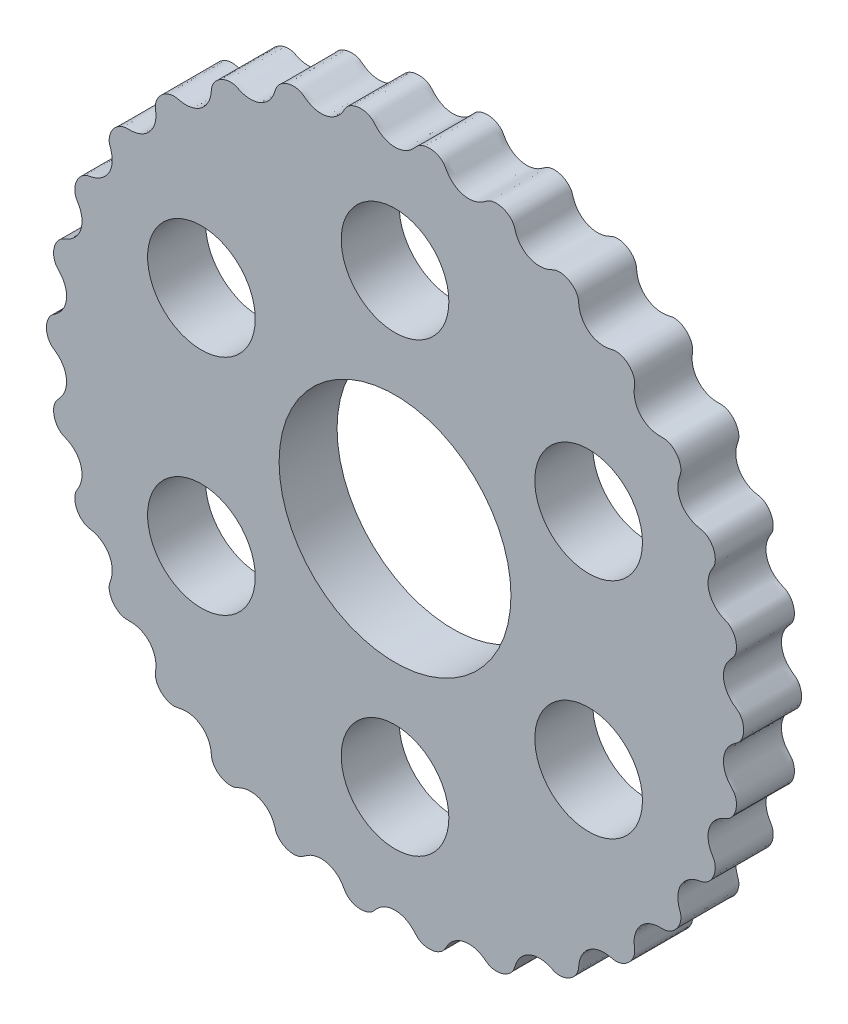
SolidWorks part; units mm, degrees
ref_plane "Front Plane" through (0, 0, 0) normal (0, 0, 1) x (1, 0, 0)
ref_plane "Top Plane" through (0, 0, 0) normal (0, 1, 0) x (1, 0, 0)
ref_plane "Right Plane" through (0, 0, 0) normal (1, 0, 0) x (0, 0, -1)
curve "Curve1"
sketch "Sketch1" plane through (0, 0, 0) normal (0, 0, 1) x (1, 0, 0)
  spline S0 degree 3 poles (1.5393, 40.2126) (0, 39.6745) (-1.5393, 40.2126) (-2.2507, 40.8811) (-2.5061, 41.1764) (-2.6357, 41.3187) (-2.7477, 41.4234) (-2.8793, 41.5246) (-3.0465, 41.6272) (-3.2548, 41.7248) (-3.5028, 41.8074) (-3.7839, 41.865) (-4.0877, 41.8894) (-4.4013, 41.8758) (-4.7109, 41.8238) (-5.003, 41.7368) (-5.266, 41.6221) (-5.4914, 41.4897) (-5.6748, 41.3509) (-5.8171, 41.2159) (-5.9248, 41.0895) (-6.0125, 40.9638) (-6.1097, 40.7977) (-6.2982, 40.4556) (-6.855, 39.6539) (-8.2488, 38.8075) (-9.8664, 39.0138) (-10.7011, 39.5198) (-11.0124, 39.7556) (-11.1688, 39.8678) (-11.3, 39.947) (-11.4498, 40.0186) (-11.6347, 40.0841) (-11.8588, 40.1363) (-12.1185, 40.1655) (-12.4054, 40.1634) (-12.7077, 40.1241) (-13.0116, 40.0457) (-13.3036, 39.9304) (-13.5712, 39.7846) (-13.8046, 39.6177) (-13.9976, 39.4413) (-14.1482, 39.2674) (-14.2592, 39.1058) (-14.3383, 38.9598) (-14.398, 38.8186) (-14.4585, 38.6359) (-14.5717, 38.2621) (-14.9497, 37.3621) (-16.1371, 36.2445) (-17.7622, 36.1099) (-18.6839, 36.4313) (-19.0374, 36.5972) (-19.2137, 36.6745) (-19.3585, 36.7246) (-19.52, 36.7635) (-19.7144, 36.7892) (-19.9444, 36.7936) (-20.2046, 36.7683) (-20.4848, 36.7065) (-20.7722, 36.6052) (-21.0533, 36.4653) (-21.3149, 36.2919) (-21.5464, 36.0936) (-21.74, 35.8818) (-21.892, 35.6692) (-22.0032, 35.4678) (-22.0782, 35.2865) (-22.1252, 35.1273) (-22.1542, 34.9768) (-22.1754, 34.7855) (-22.2085, 34.3964) (-22.391, 33.4375) (-23.3201, 32.0974) (-24.8817, 31.6279) (-25.8501, 31.7506) (-26.2304, 31.8394) (-26.4189, 31.8783) (-26.571, 31.8972) (-26.737, 31.9017) (-26.9325, 31.8864) (-27.1584, 31.8429) (-27.4076, 31.764) (-27.6689, 31.6453) (-27.929, 31.4865) (-28.1748, 31.2912) (-28.3946, 31.0672) (-28.5798, 30.8251) (-28.7251, 30.5777) (-28.8297, 30.3381) (-28.8965, 30.118) (-28.9322, 29.9251) (-28.9451, 29.7596) (-28.9421, 29.6064) (-28.9231, 29.4148) (-28.8746, 29.0273) (-28.8538, 28.0514) (-29.4839, 26.5474) (-30.9138, 25.7636) (-31.8865, 25.6822) (-32.277, 25.69) (-32.4695, 25.6889) (-32.6222, 25.6758) (-32.7854, 25.6457) (-32.9735, 25.59) (-33.1855, 25.5005) (-33.4128, 25.3715) (-33.6437, 25.2011) (-33.8651, 24.9917) (-34.0649, 24.7496) (-34.2334, 24.4847) (-34.3642, 24.2094) (-34.4549, 23.9372) (-34.5073, 23.6811) (-34.5269, 23.4519) (-34.5217, 23.2559) (-34.4999, 23.0913) (-34.4652, 22.942) (-34.4068, 22.7586) (-34.2787, 22.3897) (-34.0555, 21.4394) (-34.3591, 19.8373) (-35.5948, 18.7732) (-36.5294, 18.4914) (-36.9129, 18.4179) (-37.1009, 18.3767) (-37.2476, 18.3322) (-37.401, 18.2688) (-37.5734, 18.1752) (-37.7621, 18.0436) (-37.9577, 17.8702) (-38.1481, 17.6555) (-38.3211, 17.4046) (-38.4662, 17.1263) (-38.576, 16.8322) (-38.6467, 16.5357) (-38.6788, 16.2506) (-38.6768, 15.9892) (-38.6484, 15.7609) (-38.6025, 15.5702) (-38.547, 15.4137) (-38.482, 15.2749) (-38.3867, 15.1077) (-38.1847, 14.7734) (-37.7688, 13.8904) (-37.7327, 12.2601) (-38.7201, 10.9624) (-39.5757, 10.4924) (-39.9356, 10.3408) (-40.1109, 10.2614) (-40.2451, 10.1874) (-40.382, 10.0934) (-40.5312, 9.9661) (-40.6884, 9.7981) (-40.8437, 9.5878) (-40.9852, 9.3383) (-41.1023, 9.0569) (-41.1864, 8.7544) (-41.2326, 8.4439) (-41.2401, 8.1393) (-41.2123, 7.8537) (-41.156, 7.5984) (-41.0807, 7.381) (-40.9962, 7.204) (-40.9093, 7.0625) (-40.8169, 6.9403) (-40.6889, 6.7965) (-40.4219, 6.5116) (-39.8314, 5.7343) (-39.4572, 4.1471) (-40.1532, 2.6725) (-40.8924, 2.0349) (-41.2128, 1.8117) (-41.3679, 1.6977) (-41.4837, 1.5973) (-41.5981, 1.477) (-41.7176, 1.3214) (-41.8364, 1.1244) (-41.9445, 0.8864) (-42.0312, 0.6129) (-42.0872, 0.3133) (-42.1065, 0) (-42.0872, -0.3133) (-42.0312, -0.6129) (-41.9445, -0.8864) (-41.8364, -1.1244) (-41.7176, -1.3214) (-41.5981, -1.477) (-41.4837, -1.5973) (-41.3679, -1.6977) (-41.2128, -1.8117) (-40.8924, -2.0349) (-40.1532, -2.6725) (-39.4572, -4.1471) (-39.8314, -5.7343) (-40.4219, -6.5116) (-40.6889, -6.7965) (-40.8169, -6.9403) (-40.9093, -7.0625) (-40.9962, -7.204) (-41.0807, -7.381) (-41.156, -7.5984) (-41.2123, -7.8537) (-41.2401, -8.1393) (-41.2326, -8.4439) (-41.1864, -8.7544) (-41.1023, -9.0569) (-40.9852, -9.3383) (-40.8437, -9.5878) (-40.6884, -9.7981) (-40.5312, -9.9661) (-40.382, -10.0934) (-40.2451, -10.1874) (-40.1109, -10.2614) (-39.9356, -10.3408) (-39.5757, -10.4924) (-38.7201, -10.9624) (-37.7327, -12.2601) (-37.7688, -13.8904) (-38.1847, -14.7734) (-38.3867, -15.1077) (-38.482, -15.2749) (-38.547, -15.4137) (-38.6025, -15.5702) (-38.6484, -15.7609) (-38.6768, -15.9892) (-38.6788, -16.2506) (-38.6467, -16.5357) (-38.576, -16.8322) (-38.4662, -17.1263) (-38.3211, -17.4046) (-38.1481, -17.6555) (-37.9577, -17.8702) (-37.7621, -18.0436) (-37.5734, -18.1752) (-37.401, -18.2688) (-37.2476, -18.3322) (-37.1009, -18.3767) (-36.9129, -18.4179) (-36.5294, -18.4914) (-35.5948, -18.7732) (-34.3591, -19.8373) (-34.0555, -21.4394) (-34.2787, -22.3897) (-34.4068, -22.7586) (-34.4652, -22.942) (-34.4999, -23.0913) (-34.5217, -23.2559) (-34.5269, -23.4519) (-34.5073, -23.6811) (-34.4549, -23.9372) (-34.3642, -24.2094) (-34.2334, -24.4847) (-34.0649, -24.7496) (-33.8651, -24.9917) (-33.6437, -25.2011) (-33.4128, -25.3715) (-33.1855, -25.5005) (-32.9735, -25.59) (-32.7854, -25.6457) (-32.6222, -25.6758) (-32.4695, -25.6889) (-32.277, -25.69) (-31.8865, -25.6822) (-30.9138, -25.7636) (-29.4839, -26.5474) (-28.8538, -28.0514) (-28.8746, -29.0273) (-28.9231, -29.4148) (-28.9421, -29.6064) (-28.9451, -29.7596) (-28.9322, -29.9251) (-28.8965, -30.118) (-28.8297, -30.3381) (-28.7251, -30.5777) (-28.5798, -30.8251) (-28.3946, -31.0672) (-28.1748, -31.2912) (-27.929, -31.4865) (-27.6689, -31.6453) (-27.4076, -31.764) (-27.1584, -31.8429) (-26.9325, -31.8864) (-26.737, -31.9017) (-26.571, -31.8972) (-26.4189, -31.8783) (-26.2304, -31.8394) (-25.8501, -31.7506) (-24.8817, -31.6279) (-23.3201, -32.0974) (-22.391, -33.4375) (-22.2085, -34.3964) (-22.1754, -34.7855) (-22.1542, -34.9768) (-22.1252, -35.1273) (-22.0782, -35.2865) (-22.0032, -35.4678) (-21.892, -35.6692) (-21.74, -35.8818) (-21.5464, -36.0936) (-21.3149, -36.2919) (-21.0533, -36.4653) (-20.7722, -36.6052) (-20.4848, -36.7065) (-20.2046, -36.7683) (-19.9444, -36.7936) (-19.7144, -36.7892) (-19.52, -36.7635) (-19.3585, -36.7246) (-19.2137, -36.6745) (-19.0374, -36.5972) (-18.6839, -36.4313) (-17.7622, -36.1099) (-16.1371, -36.2445) (-14.9497, -37.3621) (-14.5717, -38.2621) (-14.4585, -38.6359) (-14.398, -38.8186) (-14.3383, -38.9598) (-14.2592, -39.1058) (-14.1482, -39.2674) (-13.9976, -39.4413) (-13.8046, -39.6177) (-13.5712, -39.7846) (-13.3036, -39.9304) (-13.0116, -40.0457) (-12.7077, -40.1241) (-12.4054, -40.1634) (-12.1185, -40.1655) (-11.8588, -40.1363) (-11.6347, -40.0841) (-11.4498, -40.0186) (-11.3, -39.947) (-11.1688, -39.8678) (-11.0124, -39.7556) (-10.7011, -39.5198) (-9.8664, -39.0138) (-8.2488, -38.8075) (-6.855, -39.6539) (-6.2982, -40.4556) (-6.1097, -40.7977) (-6.0125, -40.9638) (-5.9248, -41.0895) (-5.8171, -41.2159) (-5.6748, -41.3509) (-5.4914, -41.4897) (-5.266, -41.6221) (-5.003, -41.7368) (-4.7109, -41.8238) (-4.4013, -41.8758) (-4.0877, -41.8894) (-3.7839, -41.865) (-3.5028, -41.8074) (-3.2548, -41.7248) (-3.0465, -41.6272) (-2.8793, -41.5246) (-2.7477, -41.4234) (-2.6357, -41.3187) (-2.5061, -41.1764) (-2.2507, -40.8811) (-1.5393, -40.2126) (0, -39.6745) (1.5393, -40.2126) (2.2507, -40.8811) (2.5061, -41.1764) (2.6357, -41.3187) (2.7477, -41.4234) (2.8793, -41.5246) (3.0465, -41.6272) (3.2548, -41.7248) (3.5028, -41.8074) (3.7839, -41.865) (4.0877, -41.8894) (4.4013, -41.8758) (4.7109, -41.8238) (5.003, -41.7368) (5.266, -41.6221) (5.4914, -41.4897) (5.6748, -41.3509) (5.8171, -41.2159) (5.9248, -41.0895) (6.0125, -40.9638) (6.1097, -40.7977) (6.2982, -40.4556) (6.855, -39.6539) (8.2488, -38.8075) (9.8664, -39.0138) (10.7011, -39.5198) (11.0124, -39.7556) (11.1688, -39.8678) (11.3, -39.947) (11.4498, -40.0186) (11.6347, -40.0841) (11.8588, -40.1363) (12.1185, -40.1655) (12.4054, -40.1634) (12.7077, -40.1241) (13.0116, -40.0457) (13.3036, -39.9304) (13.5712, -39.7846) (13.8046, -39.6177) (13.9976, -39.4413) (14.1482, -39.2674) (14.2592, -39.1058) (14.3383, -38.9598) (14.398, -38.8186) (14.4585, -38.6359) (14.5717, -38.2621) (14.9497, -37.3621) (16.1371, -36.2445) (17.7622, -36.1099) (18.6839, -36.4313) (19.0374, -36.5972) (19.2137, -36.6745) (19.3585, -36.7246) (19.52, -36.7635) (19.7144, -36.7892) (19.9444, -36.7936) (20.2046, -36.7683) (20.4848, -36.7065) (20.7722, -36.6052) (21.0533, -36.4653) (21.3149, -36.2919) (21.5464, -36.0936) (21.74, -35.8818) (21.892, -35.6692) (22.0032, -35.4678) (22.0782, -35.2865) (22.1252, -35.1273) (22.1542, -34.9768) (22.1754, -34.7855) (22.2085, -34.3964) (22.391, -33.4375) (23.3201, -32.0974) (24.8817, -31.6279) (25.8501, -31.7506) (26.2304, -31.8394) (26.4189, -31.8783) (26.571, -31.8972) (26.737, -31.9017) (26.9325, -31.8864) (27.1584, -31.8429) (27.4076, -31.764) (27.6689, -31.6453) (27.929, -31.4865) (28.1748, -31.2912) (28.3946, -31.0672) (28.5798, -30.8251) (28.7251, -30.5777) (28.8297, -30.3381) (28.8965, -30.118) (28.9322, -29.9251) (28.9451, -29.7596) (28.9421, -29.6064) (28.9231, -29.4148) (28.8746, -29.0273) (28.8538, -28.0514) (29.4839, -26.5474) (30.9138, -25.7636) (31.8865, -25.6822) (32.277, -25.69) (32.4695, -25.6889) (32.6222, -25.6758) (32.7854, -25.6457) (32.9735, -25.59) (33.1855, -25.5005) (33.4128, -25.3715) (33.6437, -25.2011) (33.8651, -24.9917) (34.0649, -24.7496) (34.2334, -24.4847) (34.3642, -24.2094) (34.4549, -23.9372) (34.5073, -23.6811) (34.5269, -23.4519) (34.5217, -23.2559) (34.4999, -23.0913) (34.4652, -22.942) (34.4068, -22.7586) (34.2787, -22.3897) (34.0555, -21.4394) (34.3591, -19.8373) (35.5948, -18.7732) (36.5294, -18.4914) (36.9129, -18.4179) (37.1009, -18.3767) (37.2476, -18.3322) (37.401, -18.2688) (37.5734, -18.1752) (37.7621, -18.0436) (37.9577, -17.8702) (38.1481, -17.6555) (38.3211, -17.4046) (38.4662, -17.1263) (38.576, -16.8322) (38.6467, -16.5357) (38.6788, -16.2506) (38.6768, -15.9892) (38.6484, -15.7609) (38.6025, -15.5702) (38.547, -15.4137) (38.482, -15.2749) (38.3867, -15.1077) (38.1847, -14.7734) (37.7688, -13.8904) (37.7327, -12.2601) (38.7201, -10.9624) (39.5757, -10.4924) (39.9356, -10.3408) (40.1109, -10.2614) (40.2451, -10.1874) (40.382, -10.0934) (40.5312, -9.9661) (40.6884, -9.7981) (40.8437, -9.5878) (40.9852, -9.3383) (41.1023, -9.0569) (41.1864, -8.7544) (41.2326, -8.4439) (41.2401, -8.1393) (41.2123, -7.8537) (41.156, -7.5984) (41.0807, -7.381) (40.9962, -7.204) (40.9093, -7.0625) (40.8169, -6.9403) (40.6889, -6.7965) (40.4219, -6.5116) (39.8314, -5.7343) (39.4572, -4.1471) (40.1532, -2.6725) (40.8924, -2.0349) (41.2128, -1.8117) (41.3679, -1.6977) (41.4837, -1.5973) (41.5981, -1.477) (41.7176, -1.3214) (41.8364, -1.1244) (41.9445, -0.8864) (42.0312, -0.6129) (42.0872, -0.3133) (42.1065, 0) (42.0872, 0.3133) (42.0312, 0.6129) (41.9445, 0.8864) (41.8364, 1.1244) (41.7176, 1.3214) (41.5981, 1.477) (41.4837, 1.5973) (41.3679, 1.6977) (41.2128, 1.8117) (40.8924, 2.0349) (40.1532, 2.6725) (39.4572, 4.1471) (39.8314, 5.7343) (40.4219, 6.5116) (40.6889, 6.7965) (40.8169, 6.9403) (40.9093, 7.0625) (40.9962, 7.204) (41.0807, 7.381) (41.156, 7.5984) (41.2123, 7.8537) (41.2401, 8.1393) (41.2326, 8.4439) (41.1864, 8.7544) (41.1023, 9.0569) (40.9852, 9.3383) (40.8437, 9.5878) (40.6884, 9.7981) (40.5312, 9.9661) (40.382, 10.0934) (40.2451, 10.1874) (40.1109, 10.2614) (39.9356, 10.3408) (39.5757, 10.4924) (38.7201, 10.9624) (37.7327, 12.2601) (37.7688, 13.8904) (38.1847, 14.7734) (38.3867, 15.1077) (38.482, 15.2749) (38.547, 15.4137) (38.6025, 15.5702) (38.6484, 15.7609) (38.6768, 15.9892) (38.6788, 16.2506) (38.6467, 16.5357) (38.576, 16.8322) (38.4662, 17.1263) (38.3211, 17.4046) (38.1481, 17.6555) (37.9577, 17.8702) (37.7621, 18.0436) (37.5734, 18.1752) (37.401, 18.2688) (37.2476, 18.3322) (37.1009, 18.3767) (36.9129, 18.4179) (36.5294, 18.4914) (35.5948, 18.7732) (34.3591, 19.8373) (34.0555, 21.4394) (34.2787, 22.3897) (34.4068, 22.7586) (34.4652, 22.942) (34.4999, 23.0913) (34.5217, 23.2559) (34.5269, 23.4519) (34.5073, 23.6811) (34.4549, 23.9372) (34.3642, 24.2094) (34.2334, 24.4847) (34.0649, 24.7496) (33.8651, 24.9917) (33.6437, 25.2011) (33.4128, 25.3715) (33.1855, 25.5005) (32.9735, 25.59) (32.7854, 25.6457) (32.6222, 25.6758) (32.4695, 25.6889) (32.277, 25.69) (31.8865, 25.6822) (30.9138, 25.7636) (29.4839, 26.5474) (28.8538, 28.0514) (28.8746, 29.0273) (28.9231, 29.4148) (28.9421, 29.6064) (28.9451, 29.7596) (28.9322, 29.9251) (28.8965, 30.118) (28.8297, 30.3381) (28.7251, 30.5777) (28.5798, 30.8251) (28.3946, 31.0672) (28.1748, 31.2912) (27.929, 31.4865) (27.6689, 31.6453) (27.4076, 31.764) (27.1584, 31.8429) (26.9325, 31.8864) (26.737, 31.9017) (26.571, 31.8972) (26.4189, 31.8783) (26.2304, 31.8394) (25.8501, 31.7506) (24.8817, 31.6279) (23.3201, 32.0974) (22.391, 33.4375) (22.2085, 34.3964) (22.1754, 34.7855) (22.1542, 34.9768) (22.1252, 35.1273) (22.0782, 35.2865) (22.0032, 35.4678) (21.892, 35.6692) (21.74, 35.8818) (21.5464, 36.0936) (21.3149, 36.2919) (21.0533, 36.4653) (20.7722, 36.6052) (20.4848, 36.7065) (20.2046, 36.7683) (19.9444, 36.7936) (19.7144, 36.7892) (19.52, 36.7635) (19.3585, 36.7246) (19.2137, 36.6745) (19.0374, 36.5972) (18.6839, 36.4313) (17.7622, 36.1099) (16.1371, 36.2445) (14.9497, 37.3621) (14.5717, 38.2621) (14.4585, 38.6359) (14.398, 38.8186) (14.3383, 38.9598) (14.2592, 39.1058) (14.1482, 39.2674) (13.9976, 39.4413) (13.8046, 39.6177) (13.5712, 39.7846) (13.3036, 39.9304) (13.0116, 40.0457) (12.7077, 40.1241) (12.4054, 40.1634) (12.1185, 40.1655) (11.8588, 40.1363) (11.6347, 40.0841) (11.4498, 40.0186) (11.3, 39.947) (11.1688, 39.8678) (11.0124, 39.7556) (10.7011, 39.5198) (9.8664, 39.0138) (8.2488, 38.8075) (6.855, 39.6539) (6.2982, 40.4556) (6.1097, 40.7977) (6.0125, 40.9638) (5.9248, 41.0895) (5.8171, 41.2159) (5.6748, 41.3509) (5.4914, 41.4897) (5.266, 41.6221) (5.003, 41.7368) (4.7109, 41.8238) (4.4013, 41.8758) (4.0877, 41.8894) (3.7839, 41.865) (3.5028, 41.8074) (3.2548, 41.7248) (3.0465, 41.6272) (2.8793, 41.5246) (2.7477, 41.4234) (2.6357, 41.3187) (2.5061, 41.1764) (2.2507, 40.8811) (1.5393, 40.2126) (0, 39.6745) (-1.5393, 40.2126) knots -0.009769 -0.008833 -0.006371 0 0.006371 0.008833 0.009769 0.010295 0.010766 0.011307 0.01196 0.012732 0.013613 0.01458 0.015608 0.016667 0.017726 0.018753 0.019721 0.020601 0.021373 0.022027 0.022568 0.023039 0.023565 0.024501 0.026962 0.033333 0.039705 0.042166 0.043102 0.043628 0.044099 0.04464 0.045293 0.046066 0.046946 0.047913 0.048941 0.05 0.051059 0.052087 0.053054 0.053934 0.054707 0.05536 0.055901 0.056372 0.056898 0.057834 0.060295 0.066667 0.073038 0.075499 0.076435 0.076961 0.077432 0.077973 0.078627 0.079399 0.080279 0.081247 0.082274 0.083333 0.084392 0.08542 0.086387 0.087268 0.08804 0.088693 0.089234 0.089705 0.090231 0.091167 0.093629 0.1 0.106371 0.108833 0.109769 0.110295 0.110766 0.111307 0.11196 0.112732 0.113613 0.11458 0.115608 0.116667 0.117726 0.118753 0.119721 0.120601 0.121373 0.122027 0.122568 0.123039 0.123565 0.124501 0.126962 0.133333 0.139705 0.142166 0.143102 0.143628 0.144099 0.14464 0.145293 0.146066 0.146946 0.147913 0.148941 0.15 0.151059 0.152087 0.153054 0.153934 0.154707 0.15536 0.155901 0.156372 0.156898 0.157834 0.160295 0.166667 0.173038 0.175499 0.176435 0.176961 0.177432 0.177973 0.178627 0.179399 0.180279 0.181247 0.182274 0.183333 0.184392 0.18542 0.186387 0.187268 0.18804 0.188693 0.189234 0.189705 0.190231 0.191167 0.193629 0.2 0.206371 0.208833 0.209769 0.210295 0.210766 0.211306 0.21196 0.212732 0.213613 0.21458 0.215608 0.216667 0.217726 0.218753 0.219721 0.220601 0.221373 0.222027 0.222568 0.223039 0.223565 0.224501 0.226962 0.233333 0.239705 0.242166 0.243102 0.243628 0.244099 0.24464 0.245293 0.246066 0.246946 0.247913 0.248941 0.25 0.251059 0.252087 0.253054 0.253934 0.254707 0.25536 0.255901 0.256372 0.256898 0.257834 0.260295 0.266667 0.273038 0.275499 0.276435 0.276961 0.277432 0.277973 0.278627 0.279399 0.280279 0.281247 0.282274 0.283333 0.284392 0.28542 0.286387 0.287268 0.28804 0.288694 0.289234 0.289705 0.290231 0.291167 0.293629 0.3 0.306371 0.308833 0.309769 0.310295 0.310766 0.311307 0.31196 0.312732 0.313613 0.31458 0.315608 0.316667 0.317726 0.318753 0.319721 0.320601 0.321373 0.322027 0.322568 0.323039 0.323565 0.324501 0.326962 0.333333 0.339705 0.342166 0.343102 0.343628 0.344099 0.34464 0.345293 0.346066 0.346946 0.347913 0.348941 0.35 0.351059 0.352087 0.353054 0.353934 0.354707 0.35536 0.355901 0.356372 0.356898 0.357834 0.360295 0.366667 0.373038 0.375499 0.376435 0.376961 0.377432 0.377973 0.378627 0.379399 0.380279 0.381247 0.382274 0.383333 0.384392 0.38542 0.386387 0.387268 0.38804 0.388693 0.389234 0.389705 0.390231 0.391167 0.393629 0.4 0.406371 0.408833 0.409769 0.410295 0.410766 0.411307 0.41196 0.412732 0.413613 0.41458 0.415608 0.416667 0.417726 0.418753 0.419721 0.420601 0.421373 0.422027 0.422568 0.423039 0.423565 0.424501 0.426962 0.433333 0.439705 0.442166 0.443102 0.443628 0.444099 0.44464 0.445293 0.446066 0.446946 0.447913 0.448941 0.45 0.451059 0.452087 0.453054 0.453934 0.454707 0.45536 0.455901 0.456372 0.456898 0.457834 0.460295 0.466667 0.473038 0.475499 0.476435 0.476961 0.477432 0.477973 0.478627 0.479399 0.480279 0.481247 0.482274 0.483333 0.484392 0.48542 0.486387 0.487268 0.48804 0.488693 0.489234 0.489705 0.490231 0.491167 0.493629 0.5 0.506371 0.508833 0.509769 0.510295 0.510766 0.511307 0.51196 0.512732 0.513613 0.51458 0.515608 0.516667 0.517726 0.518753 0.519721 0.520601 0.521373 0.522027 0.522568 0.523039 0.523565 0.524501 0.526962 0.533333 0.539705 0.542166 0.543102 0.543628 0.544099 0.54464 0.545293 0.546066 0.546946 0.547913 0.548941 0.55 0.551059 0.552087 0.553054 0.553934 0.554707 0.55536 0.555901 0.556372 0.556898 0.557834 0.560295 0.566667 0.573038 0.575499 0.576435 0.576961 0.577432 0.577973 0.578627 0.579399 0.580279 0.581247 0.582274 0.583333 0.584392 0.58542 0.586387 0.587268 0.58804 0.588693 0.589234 0.589705 0.590231 0.591167 0.593629 0.6 0.606371 0.608833 0.609769 0.610295 0.610766 0.611307 0.61196 0.612732 0.613613 0.61458 0.615608 0.616667 0.617726 0.618753 0.619721 0.620601 0.621373 0.622027 0.622568 0.623039 0.623565 0.624501 0.626962 0.633333 0.639705 0.642166 0.643102 0.643628 0.644099 0.64464 0.645293 0.646066 0.646946 0.647913 0.648941 0.65 0.651059 0.652087 0.653054 0.653934 0.654707 0.65536 0.655901 0.656372 0.656898 0.657834 0.660295 0.666667 0.673038 0.675499 0.676435 0.676961 0.677432 0.677973 0.678627 0.679399 0.680279 0.681247 0.682274 0.683333 0.684392 0.68542 0.686387 0.687268 0.68804 0.688693 0.689234 0.689705 0.690231 0.691167 0.693629 0.7 0.706371 0.708833 0.709769 0.710295 0.710766 0.711306 0.71196 0.712732 0.713613 0.71458 0.715608 0.716667 0.717726 0.718753 0.719721 0.720601 0.721373 0.722027 0.722568 0.723039 0.723565 0.724501 0.726962 0.733333 0.739705 0.742166 0.743102 0.743628 0.744099 0.74464 0.745293 0.746066 0.746946 0.747913 0.748941 0.75 0.751059 0.752087 0.753054 0.753934 0.754707 0.75536 0.755901 0.756372 0.756898 0.757834 0.760295 0.766667 0.773038 0.775499 0.776435 0.776961 0.777432 0.777973 0.778627 0.779399 0.780279 0.781247 0.782274 0.783333 0.784392 0.78542 0.786387 0.787268 0.78804 0.788694 0.789234 0.789705 0.790231 0.791167 0.793629 0.8 0.806371 0.808833 0.809769 0.810295 0.810766 0.811307 0.81196 0.812732 0.813613 0.81458 0.815608 0.816667 0.817726 0.818753 0.819721 0.820601 0.821373 0.822027 0.822568 0.823039 0.823565 0.824501 0.826962 0.833333 0.839705 0.842166 0.843102 0.843628 0.844099 0.84464 0.845293 0.846066 0.846946 0.847913 0.848941 0.85 0.851059 0.852087 0.853054 0.853934 0.854707 0.85536 0.855901 0.856372 0.856898 0.857834 0.860295 0.866667 0.873038 0.875499 0.876435 0.876961 0.877432 0.877973 0.878627 0.879399 0.880279 0.881247 0.882274 0.883333 0.884392 0.88542 0.886387 0.887268 0.88804 0.888693 0.889234 0.889705 0.890231 0.891167 0.893629 0.9 0.906371 0.908833 0.909769 0.910295 0.910766 0.911307 0.91196 0.912732 0.913613 0.91458 0.915608 0.916667 0.917726 0.918753 0.919721 0.920601 0.921373 0.922027 0.922568 0.923039 0.923565 0.924501 0.926962 0.933333 0.939705 0.942166 0.943102 0.943628 0.944099 0.94464 0.945293 0.946066 0.946946 0.947913 0.948941 0.95 0.951059 0.952087 0.953054 0.953934 0.954707 0.95536 0.955901 0.956372 0.956898 0.957834 0.960295 0.966667 0.973038 0.975499 0.976435 0.976961 0.977432 0.977973 0.978627 0.979399 0.980279 0.981247 0.982274 0.983333 0.984392 0.98542 0.986387 0.987268 0.98804 0.988693 0.989234 0.989705 0.990231 0.991167 0.993629 1 1.006371 1.008833 1.009769 only from (0, 39.9) to (0, 39.9) construction
  spline S1 degree 3 poles (1.5393, 40.2126) (0, 39.6745) (-1.5393, 40.2126) (-2.2507, 40.8811) (-2.5061, 41.1764) (-2.6357, 41.3187) (-2.7477, 41.4234) (-2.8793, 41.5246) (-3.0465, 41.6272) (-3.2548, 41.7248) (-3.5028, 41.8074) (-3.7839, 41.865) (-4.0877, 41.8894) (-4.4013, 41.8758) (-4.7109, 41.8238) (-5.003, 41.7368) (-5.266, 41.6221) (-5.4914, 41.4897) (-5.6748, 41.3509) (-5.8171, 41.2159) (-5.9248, 41.0895) (-6.0125, 40.9638) (-6.1097, 40.7977) (-6.2982, 40.4556) (-6.855, 39.6539) (-8.2488, 38.8075) (-9.8664, 39.0138) (-10.7011, 39.5198) (-11.0124, 39.7556) (-11.1688, 39.8678) (-11.3, 39.947) (-11.4498, 40.0186) (-11.6347, 40.0841) (-11.8588, 40.1363) (-12.1185, 40.1655) (-12.4054, 40.1634) (-12.7077, 40.1241) (-13.0116, 40.0457) (-13.3036, 39.9304) (-13.5712, 39.7846) (-13.8046, 39.6177) (-13.9976, 39.4413) (-14.1482, 39.2674) (-14.2592, 39.1058) (-14.3383, 38.9598) (-14.398, 38.8186) (-14.4585, 38.6359) (-14.5717, 38.2621) (-14.9497, 37.3621) (-16.1371, 36.2445) (-17.7622, 36.1099) (-18.6839, 36.4313) (-19.0374, 36.5972) (-19.2137, 36.6745) (-19.3585, 36.7246) (-19.52, 36.7635) (-19.7144, 36.7892) (-19.9444, 36.7936) (-20.2046, 36.7683) (-20.4848, 36.7065) (-20.7722, 36.6052) (-21.0533, 36.4653) (-21.3149, 36.2919) (-21.5464, 36.0936) (-21.74, 35.8818) (-21.892, 35.6692) (-22.0032, 35.4678) (-22.0782, 35.2865) (-22.1252, 35.1273) (-22.1542, 34.9768) (-22.1754, 34.7855) (-22.2085, 34.3964) (-22.391, 33.4375) (-23.3201, 32.0974) (-24.8817, 31.6279) (-25.8501, 31.7506) (-26.2304, 31.8394) (-26.4189, 31.8783) (-26.571, 31.8972) (-26.737, 31.9017) (-26.9325, 31.8864) (-27.1584, 31.8429) (-27.4076, 31.764) (-27.6689, 31.6453) (-27.929, 31.4865) (-28.1748, 31.2912) (-28.3946, 31.0672) (-28.5798, 30.8251) (-28.7251, 30.5777) (-28.8297, 30.3381) (-28.8965, 30.118) (-28.9322, 29.9251) (-28.9451, 29.7596) (-28.9421, 29.6064) (-28.9231, 29.4148) (-28.8746, 29.0273) (-28.8538, 28.0514) (-29.4839, 26.5474) (-30.9138, 25.7636) (-31.8865, 25.6822) (-32.277, 25.69) (-32.4695, 25.6889) (-32.6222, 25.6758) (-32.7854, 25.6457) (-32.9735, 25.59) (-33.1855, 25.5005) (-33.4128, 25.3715) (-33.6437, 25.2011) (-33.8651, 24.9917) (-34.0649, 24.7496) (-34.2334, 24.4847) (-34.3642, 24.2094) (-34.4549, 23.9372) (-34.5073, 23.6811) (-34.5269, 23.4519) (-34.5217, 23.2559) (-34.4999, 23.0913) (-34.4652, 22.942) (-34.4068, 22.7586) (-34.2787, 22.3897) (-34.0555, 21.4394) (-34.3591, 19.8373) (-35.5948, 18.7732) (-36.5294, 18.4914) (-36.9129, 18.4179) (-37.1009, 18.3767) (-37.2476, 18.3322) (-37.401, 18.2688) (-37.5734, 18.1752) (-37.7621, 18.0436) (-37.9577, 17.8702) (-38.1481, 17.6555) (-38.3211, 17.4046) (-38.4662, 17.1263) (-38.576, 16.8322) (-38.6467, 16.5357) (-38.6788, 16.2506) (-38.6768, 15.9892) (-38.6484, 15.7609) (-38.6025, 15.5702) (-38.547, 15.4137) (-38.482, 15.2749) (-38.3867, 15.1077) (-38.1847, 14.7734) (-37.7688, 13.8904) (-37.7327, 12.2601) (-38.7201, 10.9624) (-39.5757, 10.4924) (-39.9356, 10.3408) (-40.1109, 10.2614) (-40.2451, 10.1874) (-40.382, 10.0934) (-40.5312, 9.9661) (-40.6884, 9.7981) (-40.8437, 9.5878) (-40.9852, 9.3383) (-41.1023, 9.0569) (-41.1864, 8.7544) (-41.2326, 8.4439) (-41.2401, 8.1393) (-41.2123, 7.8537) (-41.156, 7.5984) (-41.0807, 7.381) (-40.9962, 7.204) (-40.9093, 7.0625) (-40.8169, 6.9403) (-40.6889, 6.7965) (-40.4219, 6.5116) (-39.8314, 5.7343) (-39.4572, 4.1471) (-40.1532, 2.6725) (-40.8924, 2.0349) (-41.2128, 1.8117) (-41.3679, 1.6977) (-41.4837, 1.5973) (-41.5981, 1.477) (-41.7176, 1.3214) (-41.8364, 1.1244) (-41.9445, 0.8864) (-42.0312, 0.6129) (-42.0872, 0.3133) (-42.1065, 0) (-42.0872, -0.3133) (-42.0312, -0.6129) (-41.9445, -0.8864) (-41.8364, -1.1244) (-41.7176, -1.3214) (-41.5981, -1.477) (-41.4837, -1.5973) (-41.3679, -1.6977) (-41.2128, -1.8117) (-40.8924, -2.0349) (-40.1532, -2.6725) (-39.4572, -4.1471) (-39.8314, -5.7343) (-40.4219, -6.5116) (-40.6889, -6.7965) (-40.8169, -6.9403) (-40.9093, -7.0625) (-40.9962, -7.204) (-41.0807, -7.381) (-41.156, -7.5984) (-41.2123, -7.8537) (-41.2401, -8.1393) (-41.2326, -8.4439) (-41.1864, -8.7544) (-41.1023, -9.0569) (-40.9852, -9.3383) (-40.8437, -9.5878) (-40.6884, -9.7981) (-40.5312, -9.9661) (-40.382, -10.0934) (-40.2451, -10.1874) (-40.1109, -10.2614) (-39.9356, -10.3408) (-39.5757, -10.4924) (-38.7201, -10.9624) (-37.7327, -12.2601) (-37.7688, -13.8904) (-38.1847, -14.7734) (-38.3867, -15.1077) (-38.482, -15.2749) (-38.547, -15.4137) (-38.6025, -15.5702) (-38.6484, -15.7609) (-38.6768, -15.9892) (-38.6788, -16.2506) (-38.6467, -16.5357) (-38.576, -16.8322) (-38.4662, -17.1263) (-38.3211, -17.4046) (-38.1481, -17.6555) (-37.9577, -17.8702) (-37.7621, -18.0436) (-37.5734, -18.1752) (-37.401, -18.2688) (-37.2476, -18.3322) (-37.1009, -18.3767) (-36.9129, -18.4179) (-36.5294, -18.4914) (-35.5948, -18.7732) (-34.3591, -19.8373) (-34.0555, -21.4394) (-34.2787, -22.3897) (-34.4068, -22.7586) (-34.4652, -22.942) (-34.4999, -23.0913) (-34.5217, -23.2559) (-34.5269, -23.4519) (-34.5073, -23.6811) (-34.4549, -23.9372) (-34.3642, -24.2094) (-34.2334, -24.4847) (-34.0649, -24.7496) (-33.8651, -24.9917) (-33.6437, -25.2011) (-33.4128, -25.3715) (-33.1855, -25.5005) (-32.9735, -25.59) (-32.7854, -25.6457) (-32.6222, -25.6758) (-32.4695, -25.6889) (-32.277, -25.69) (-31.8865, -25.6822) (-30.9138, -25.7636) (-29.4839, -26.5474) (-28.8538, -28.0514) (-28.8746, -29.0273) (-28.9231, -29.4148) (-28.9421, -29.6064) (-28.9451, -29.7596) (-28.9322, -29.9251) (-28.8965, -30.118) (-28.8297, -30.3381) (-28.7251, -30.5777) (-28.5798, -30.8251) (-28.3946, -31.0672) (-28.1748, -31.2912) (-27.929, -31.4865) (-27.6689, -31.6453) (-27.4076, -31.764) (-27.1584, -31.8429) (-26.9325, -31.8864) (-26.737, -31.9017) (-26.571, -31.8972) (-26.4189, -31.8783) (-26.2304, -31.8394) (-25.8501, -31.7506) (-24.8817, -31.6279) (-23.3201, -32.0974) (-22.391, -33.4375) (-22.2085, -34.3964) (-22.1754, -34.7855) (-22.1542, -34.9768) (-22.1252, -35.1273) (-22.0782, -35.2865) (-22.0032, -35.4678) (-21.892, -35.6692) (-21.74, -35.8818) (-21.5464, -36.0936) (-21.3149, -36.2919) (-21.0533, -36.4653) (-20.7722, -36.6052) (-20.4848, -36.7065) (-20.2046, -36.7683) (-19.9444, -36.7936) (-19.7144, -36.7892) (-19.52, -36.7635) (-19.3585, -36.7246) (-19.2137, -36.6745) (-19.0374, -36.5972) (-18.6839, -36.4313) (-17.7622, -36.1099) (-16.1371, -36.2445) (-14.9497, -37.3621) (-14.5717, -38.2621) (-14.4585, -38.6359) (-14.398, -38.8186) (-14.3383, -38.9598) (-14.2592, -39.1058) (-14.1482, -39.2674) (-13.9976, -39.4413) (-13.8046, -39.6177) (-13.5712, -39.7846) (-13.3036, -39.9304) (-13.0116, -40.0457) (-12.7077, -40.1241) (-12.4054, -40.1634) (-12.1185, -40.1655) (-11.8588, -40.1363) (-11.6347, -40.0841) (-11.4498, -40.0186) (-11.3, -39.947) (-11.1688, -39.8678) (-11.0124, -39.7556) (-10.7011, -39.5198) (-9.8664, -39.0138) (-8.2488, -38.8075) (-6.855, -39.6539) (-6.2982, -40.4556) (-6.1097, -40.7977) (-6.0125, -40.9638) (-5.9248, -41.0895) (-5.8171, -41.2159) (-5.6748, -41.3509) (-5.4914, -41.4897) (-5.266, -41.6221) (-5.003, -41.7368) (-4.7109, -41.8238) (-4.4013, -41.8758) (-4.0877, -41.8894) (-3.7839, -41.865) (-3.5028, -41.8074) (-3.2548, -41.7248) (-3.0465, -41.6272) (-2.8793, -41.5246) (-2.7477, -41.4234) (-2.6357, -41.3187) (-2.5061, -41.1764) (-2.2507, -40.8811) (-1.5393, -40.2126) (0, -39.6745) (1.5393, -40.2126) (2.2507, -40.8811) (2.5061, -41.1764) (2.6357, -41.3187) (2.7477, -41.4234) (2.8793, -41.5246) (3.0465, -41.6272) (3.2548, -41.7248) (3.5028, -41.8074) (3.7839, -41.865) (4.0877, -41.8894) (4.4013, -41.8758) (4.7109, -41.8238) (5.003, -41.7368) (5.266, -41.6221) (5.4914, -41.4897) (5.6748, -41.3509) (5.8171, -41.2159) (5.9248, -41.0895) (6.0125, -40.9638) (6.1097, -40.7977) (6.2982, -40.4556) (6.855, -39.6539) (8.2488, -38.8075) (9.8664, -39.0138) (10.7011, -39.5198) (11.0124, -39.7556) (11.1688, -39.8678) (11.3, -39.947) (11.4498, -40.0186) (11.6347, -40.0841) (11.8588, -40.1363) (12.1185, -40.1655) (12.4054, -40.1634) (12.7077, -40.1241) (13.0116, -40.0457) (13.3036, -39.9304) (13.5712, -39.7846) (13.8046, -39.6177) (13.9976, -39.4413) (14.1482, -39.2674) (14.2592, -39.1058) (14.3383, -38.9598) (14.398, -38.8186) (14.4585, -38.6359) (14.5717, -38.2621) (14.9497, -37.3621) (16.1371, -36.2445) (17.7622, -36.1099) (18.6839, -36.4313) (19.0374, -36.5972) (19.2137, -36.6745) (19.3585, -36.7246) (19.52, -36.7635) (19.7144, -36.7892) (19.9444, -36.7936) (20.2046, -36.7683) (20.4848, -36.7065) (20.7722, -36.6052) (21.0533, -36.4653) (21.3149, -36.2919) (21.5464, -36.0936) (21.74, -35.8818) (21.892, -35.6692) (22.0032, -35.4678) (22.0782, -35.2865) (22.1252, -35.1273) (22.1542, -34.9768) (22.1754, -34.7855) (22.2085, -34.3964) (22.391, -33.4375) (23.3201, -32.0974) (24.8817, -31.6279) (25.8501, -31.7506) (26.2304, -31.8394) (26.4189, -31.8783) (26.571, -31.8972) (26.737, -31.9017) (26.9325, -31.8864) (27.1584, -31.8429) (27.4076, -31.764) (27.6689, -31.6453) (27.929, -31.4865) (28.1748, -31.2912) (28.3946, -31.0672) (28.5798, -30.8251) (28.7251, -30.5777) (28.8297, -30.3381) (28.8965, -30.118) (28.9322, -29.9251) (28.9451, -29.7596) (28.9421, -29.6064) (28.9231, -29.4148) (28.8746, -29.0273) (28.8538, -28.0514) (29.4839, -26.5474) (30.9138, -25.7636) (31.8865, -25.6822) (32.277, -25.69) (32.4695, -25.6889) (32.6222, -25.6758) (32.7854, -25.6457) (32.9735, -25.59) (33.1855, -25.5005) (33.4128, -25.3715) (33.6437, -25.2011) (33.8651, -24.9917) (34.0649, -24.7496) (34.2334, -24.4847) (34.3642, -24.2094) (34.4549, -23.9372) (34.5073, -23.6811) (34.5269, -23.4519) (34.5217, -23.2559) (34.4999, -23.0913) (34.4652, -22.942) (34.4068, -22.7586) (34.2787, -22.3897) (34.0555, -21.4394) (34.3591, -19.8373) (35.5948, -18.7732) (36.5294, -18.4914) (36.9129, -18.4179) (37.1009, -18.3767) (37.2476, -18.3322) (37.401, -18.2688) (37.5734, -18.1752) (37.7621, -18.0436) (37.9577, -17.8702) (38.1481, -17.6555) (38.3211, -17.4046) (38.4662, -17.1263) (38.576, -16.8322) (38.6467, -16.5357) (38.6788, -16.2506) (38.6768, -15.9892) (38.6484, -15.7609) (38.6025, -15.5702) (38.547, -15.4137) (38.482, -15.2749) (38.3867, -15.1077) (38.1847, -14.7734) (37.7688, -13.8904) (37.7327, -12.2601) (38.7201, -10.9624) (39.5757, -10.4924) (39.9356, -10.3408) (40.1109, -10.2614) (40.2451, -10.1874) (40.382, -10.0934) (40.5312, -9.9661) (40.6884, -9.7981) (40.8437, -9.5878) (40.9852, -9.3383) (41.1023, -9.0569) (41.1864, -8.7544) (41.2326, -8.4439) (41.2401, -8.1393) (41.2123, -7.8537) (41.156, -7.5984) (41.0807, -7.381) (40.9962, -7.204) (40.9093, -7.0625) (40.8169, -6.9403) (40.6889, -6.7965) (40.4219, -6.5116) (39.8314, -5.7343) (39.4572, -4.1471) (40.1532, -2.6725) (40.8924, -2.0349) (41.2128, -1.8117) (41.3679, -1.6977) (41.4837, -1.5973) (41.5981, -1.477) (41.7176, -1.3214) (41.8364, -1.1244) (41.9445, -0.8864) (42.0312, -0.6129) (42.0872, -0.3133) (42.1065, 0) (42.0872, 0.3133) (42.0312, 0.6129) (41.9445, 0.8864) (41.8364, 1.1244) (41.7176, 1.3214) (41.5981, 1.477) (41.4837, 1.5973) (41.3679, 1.6977) (41.2128, 1.8117) (40.8924, 2.0349) (40.1532, 2.6725) (39.4572, 4.1471) (39.8314, 5.7343) (40.4219, 6.5116) (40.6889, 6.7965) (40.8169, 6.9403) (40.9093, 7.0625) (40.9962, 7.204) (41.0807, 7.381) (41.156, 7.5984) (41.2123, 7.8537) (41.2401, 8.1393) (41.2326, 8.4439) (41.1864, 8.7544) (41.1023, 9.0569) (40.9852, 9.3383) (40.8437, 9.5878) (40.6884, 9.7981) (40.5312, 9.9661) (40.382, 10.0934) (40.2451, 10.1874) (40.1109, 10.2614) (39.9356, 10.3408) (39.5757, 10.4924) (38.7201, 10.9624) (37.7327, 12.2601) (37.7688, 13.8904) (38.1847, 14.7734) (38.3867, 15.1077) (38.482, 15.2749) (38.547, 15.4137) (38.6025, 15.5702) (38.6484, 15.7609) (38.6768, 15.9892) (38.6788, 16.2506) (38.6467, 16.5357) (38.576, 16.8322) (38.4662, 17.1263) (38.3211, 17.4046) (38.1481, 17.6555) (37.9577, 17.8702) (37.7621, 18.0436) (37.5734, 18.1752) (37.401, 18.2688) (37.2476, 18.3322) (37.1009, 18.3767) (36.9129, 18.4179) (36.5294, 18.4914) (35.5948, 18.7732) (34.3591, 19.8373) (34.0555, 21.4394) (34.2787, 22.3897) (34.4068, 22.7586) (34.4652, 22.942) (34.4999, 23.0913) (34.5217, 23.2559) (34.5269, 23.4519) (34.5073, 23.6811) (34.4549, 23.9372) (34.3642, 24.2094) (34.2334, 24.4847) (34.0649, 24.7496) (33.8651, 24.9917) (33.6437, 25.2011) (33.4128, 25.3715) (33.1855, 25.5005) (32.9735, 25.59) (32.7854, 25.6457) (32.6222, 25.6758) (32.4695, 25.6889) (32.277, 25.69) (31.8865, 25.6822) (30.9138, 25.7636) (29.4839, 26.5474) (28.8538, 28.0514) (28.8746, 29.0273) (28.9231, 29.4148) (28.9421, 29.6064) (28.9451, 29.7596) (28.9322, 29.9251) (28.8965, 30.118) (28.8297, 30.3381) (28.7251, 30.5777) (28.5798, 30.8251) (28.3946, 31.0672) (28.1748, 31.2912) (27.929, 31.4865) (27.6689, 31.6453) (27.4076, 31.764) (27.1584, 31.8429) (26.9325, 31.8864) (26.737, 31.9017) (26.571, 31.8972) (26.4189, 31.8783) (26.2304, 31.8394) (25.8501, 31.7506) (24.8817, 31.6279) (23.3201, 32.0974) (22.391, 33.4375) (22.2085, 34.3964) (22.1754, 34.7855) (22.1542, 34.9768) (22.1252, 35.1273) (22.0782, 35.2865) (22.0032, 35.4678) (21.892, 35.6692) (21.74, 35.8818) (21.5464, 36.0936) (21.3149, 36.2919) (21.0533, 36.4653) (20.7722, 36.6052) (20.4848, 36.7065) (20.2046, 36.7683) (19.9444, 36.7936) (19.7144, 36.7892) (19.52, 36.7635) (19.3585, 36.7246) (19.2137, 36.6745) (19.0374, 36.5972) (18.6839, 36.4313) (17.7622, 36.1099) (16.1371, 36.2445) (14.9497, 37.3621) (14.5717, 38.2621) (14.4585, 38.6359) (14.398, 38.8186) (14.3383, 38.9598) (14.2592, 39.1058) (14.1482, 39.2674) (13.9976, 39.4413) (13.8046, 39.6177) (13.5712, 39.7846) (13.3036, 39.9304) (13.0116, 40.0457) (12.7077, 40.1241) (12.4054, 40.1634) (12.1185, 40.1655) (11.8588, 40.1363) (11.6347, 40.0841) (11.4498, 40.0186) (11.3, 39.947) (11.1688, 39.8678) (11.0124, 39.7556) (10.7011, 39.5198) (9.8664, 39.0138) (8.2488, 38.8075) (6.855, 39.6539) (6.2982, 40.4556) (6.1097, 40.7977) (6.0125, 40.9638) (5.9248, 41.0895) (5.8171, 41.2159) (5.6748, 41.3509) (5.4914, 41.4897) (5.266, 41.6221) (5.003, 41.7368) (4.7109, 41.8238) (4.4013, 41.8758) (4.0877, 41.8894) (3.7839, 41.865) (3.5028, 41.8074) (3.2548, 41.7248) (3.0465, 41.6272) (2.8793, 41.5246) (2.7477, 41.4234) (2.6357, 41.3187) (2.5061, 41.1764) (2.2507, 40.8811) (1.5393, 40.2126) (0, 39.6745) (-1.5393, 40.2126) knots -0.009769 -0.008833 -0.006371 0 0.006371 0.008833 0.009769 0.010295 0.010766 0.011307 0.01196 0.012732 0.013613 0.01458 0.015608 0.016667 0.017726 0.018753 0.019721 0.020601 0.021373 0.022027 0.022568 0.023039 0.023565 0.024501 0.026962 0.033333 0.039705 0.042166 0.043102 0.043628 0.044099 0.04464 0.045293 0.046066 0.046946 0.047913 0.048941 0.05 0.051059 0.052087 0.053054 0.053934 0.054707 0.05536 0.055901 0.056372 0.056898 0.057834 0.060295 0.066667 0.073038 0.075499 0.076435 0.076961 0.077432 0.077973 0.078627 0.079399 0.080279 0.081247 0.082274 0.083333 0.084392 0.08542 0.086387 0.087268 0.08804 0.088693 0.089234 0.089705 0.090231 0.091167 0.093629 0.1 0.106371 0.108833 0.109769 0.110295 0.110766 0.111307 0.11196 0.112732 0.113613 0.11458 0.115608 0.116667 0.117726 0.118753 0.119721 0.120601 0.121373 0.122027 0.122568 0.123039 0.123565 0.124501 0.126962 0.133333 0.139705 0.142166 0.143102 0.143628 0.144099 0.14464 0.145293 0.146066 0.146946 0.147913 0.148941 0.15 0.151059 0.152087 0.153054 0.153934 0.154707 0.15536 0.155901 0.156372 0.156898 0.157834 0.160295 0.166667 0.173038 0.175499 0.176435 0.176961 0.177432 0.177973 0.178627 0.179399 0.180279 0.181247 0.182274 0.183333 0.184392 0.18542 0.186387 0.187268 0.18804 0.188693 0.189234 0.189705 0.190231 0.191167 0.193629 0.2 0.206371 0.208833 0.209769 0.210295 0.210766 0.211306 0.21196 0.212732 0.213613 0.21458 0.215608 0.216667 0.217726 0.218753 0.219721 0.220601 0.221373 0.222027 0.222568 0.223039 0.223565 0.224501 0.226962 0.233333 0.239705 0.242166 0.243102 0.243628 0.244099 0.24464 0.245293 0.246066 0.246946 0.247913 0.248941 0.25 0.251059 0.252087 0.253054 0.253934 0.254707 0.25536 0.255901 0.256372 0.256898 0.257834 0.260295 0.266667 0.273038 0.275499 0.276435 0.276961 0.277432 0.277973 0.278627 0.279399 0.280279 0.281247 0.282274 0.283333 0.284392 0.28542 0.286387 0.287268 0.28804 0.288694 0.289234 0.289705 0.290231 0.291167 0.293629 0.3 0.306371 0.308833 0.309769 0.310295 0.310766 0.311307 0.31196 0.312732 0.313613 0.31458 0.315608 0.316667 0.317726 0.318753 0.319721 0.320601 0.321373 0.322027 0.322568 0.323039 0.323565 0.324501 0.326962 0.333333 0.339705 0.342166 0.343102 0.343628 0.344099 0.34464 0.345293 0.346066 0.346946 0.347913 0.348941 0.35 0.351059 0.352087 0.353054 0.353934 0.354707 0.35536 0.355901 0.356372 0.356898 0.357834 0.360295 0.366667 0.373038 0.375499 0.376435 0.376961 0.377432 0.377973 0.378627 0.379399 0.380279 0.381247 0.382274 0.383333 0.384392 0.38542 0.386387 0.387268 0.38804 0.388693 0.389234 0.389705 0.390231 0.391167 0.393629 0.4 0.406371 0.408833 0.409769 0.410295 0.410766 0.411307 0.41196 0.412732 0.413613 0.41458 0.415608 0.416667 0.417726 0.418753 0.419721 0.420601 0.421373 0.422027 0.422568 0.423039 0.423565 0.424501 0.426962 0.433333 0.439705 0.442166 0.443102 0.443628 0.444099 0.44464 0.445293 0.446066 0.446946 0.447913 0.448941 0.45 0.451059 0.452087 0.453054 0.453934 0.454707 0.45536 0.455901 0.456372 0.456898 0.457834 0.460295 0.466667 0.473038 0.475499 0.476435 0.476961 0.477432 0.477973 0.478627 0.479399 0.480279 0.481247 0.482274 0.483333 0.484392 0.48542 0.486387 0.487268 0.48804 0.488693 0.489234 0.489705 0.490231 0.491167 0.493629 0.5 0.506371 0.508833 0.509769 0.510295 0.510766 0.511307 0.51196 0.512732 0.513613 0.51458 0.515608 0.516667 0.517726 0.518753 0.519721 0.520601 0.521373 0.522027 0.522568 0.523039 0.523565 0.524501 0.526962 0.533333 0.539705 0.542166 0.543102 0.543628 0.544099 0.54464 0.545293 0.546066 0.546946 0.547913 0.548941 0.55 0.551059 0.552087 0.553054 0.553934 0.554707 0.55536 0.555901 0.556372 0.556898 0.557834 0.560295 0.566667 0.573038 0.575499 0.576435 0.576961 0.577432 0.577973 0.578627 0.579399 0.580279 0.581247 0.582274 0.583333 0.584392 0.58542 0.586387 0.587268 0.58804 0.588693 0.589234 0.589705 0.590231 0.591167 0.593629 0.6 0.606371 0.608833 0.609769 0.610295 0.610766 0.611307 0.61196 0.612732 0.613613 0.61458 0.615608 0.616667 0.617726 0.618753 0.619721 0.620601 0.621373 0.622027 0.622568 0.623039 0.623565 0.624501 0.626962 0.633333 0.639705 0.642166 0.643102 0.643628 0.644099 0.64464 0.645293 0.646066 0.646946 0.647913 0.648941 0.65 0.651059 0.652087 0.653054 0.653934 0.654707 0.65536 0.655901 0.656372 0.656898 0.657834 0.660295 0.666667 0.673038 0.675499 0.676435 0.676961 0.677432 0.677973 0.678627 0.679399 0.680279 0.681247 0.682274 0.683333 0.684392 0.68542 0.686387 0.687268 0.68804 0.688693 0.689234 0.689705 0.690231 0.691167 0.693629 0.7 0.706371 0.708833 0.709769 0.710295 0.710766 0.711306 0.71196 0.712732 0.713613 0.71458 0.715608 0.716667 0.717726 0.718753 0.719721 0.720601 0.721373 0.722027 0.722568 0.723039 0.723565 0.724501 0.726962 0.733333 0.739705 0.742166 0.743102 0.743628 0.744099 0.74464 0.745293 0.746066 0.746946 0.747913 0.748941 0.75 0.751059 0.752087 0.753054 0.753934 0.754707 0.75536 0.755901 0.756372 0.756898 0.757834 0.760295 0.766667 0.773038 0.775499 0.776435 0.776961 0.777432 0.777973 0.778627 0.779399 0.780279 0.781247 0.782274 0.783333 0.784392 0.78542 0.786387 0.787268 0.78804 0.788694 0.789234 0.789705 0.790231 0.791167 0.793629 0.8 0.806371 0.808833 0.809769 0.810295 0.810766 0.811307 0.81196 0.812732 0.813613 0.81458 0.815608 0.816667 0.817726 0.818753 0.819721 0.820601 0.821373 0.822027 0.822568 0.823039 0.823565 0.824501 0.826962 0.833333 0.839705 0.842166 0.843102 0.843628 0.844099 0.84464 0.845293 0.846066 0.846946 0.847913 0.848941 0.85 0.851059 0.852087 0.853054 0.853934 0.854707 0.85536 0.855901 0.856372 0.856898 0.857834 0.860295 0.866667 0.873038 0.875499 0.876435 0.876961 0.877432 0.877973 0.878627 0.879399 0.880279 0.881247 0.882274 0.883333 0.884392 0.88542 0.886387 0.887268 0.88804 0.888693 0.889234 0.889705 0.890231 0.891167 0.893629 0.9 0.906371 0.908833 0.909769 0.910295 0.910766 0.911307 0.91196 0.912732 0.913613 0.91458 0.915608 0.916667 0.917726 0.918753 0.919721 0.920601 0.921373 0.922027 0.922568 0.923039 0.923565 0.924501 0.926962 0.933333 0.939705 0.942166 0.943102 0.943628 0.944099 0.94464 0.945293 0.946066 0.946946 0.947913 0.948941 0.95 0.951059 0.952087 0.953054 0.953934 0.954707 0.95536 0.955901 0.956372 0.956898 0.957834 0.960295 0.966667 0.973038 0.975499 0.976435 0.976961 0.977432 0.977973 0.978627 0.979399 0.980279 0.981247 0.982274 0.983333 0.984392 0.98542 0.986387 0.987268 0.98804 0.988693 0.989234 0.989705 0.990231 0.991167 0.993629 1 1.006371 1.008833 1.009769 only from (0, 39.9) to (0, 39.9)
extrude "Boss-Extrude1" add sketch "Sketch1" along normal blind 7
sketch "Sketch2" plane through (0, 0, 7) normal (0, 0, 1) x (1, 0, 0)
  circle A0 centre (0, 0) radius 14
  circle A1 centre (0, 27) radius 6.5
  circle A2 centre (23.3827, 13.5) radius 6.5
  circle A3 centre (23.3827, -13.5) radius 6.5
  circle A4 centre (0, -27) radius 6.5
  circle A5 centre (-23.3827, -13.5) radius 6.5
  circle A6 centre (-23.3827, 13.5) radius 6.5
  point P17 (0, 0)
  dimension "D1" = 28
  dimension "D2" = 13
  dimension "D3" = 27
  dimension "D4" = 6
extrude "Cut-Extrude1" cut sketch "Sketch2" against normal blind 7
